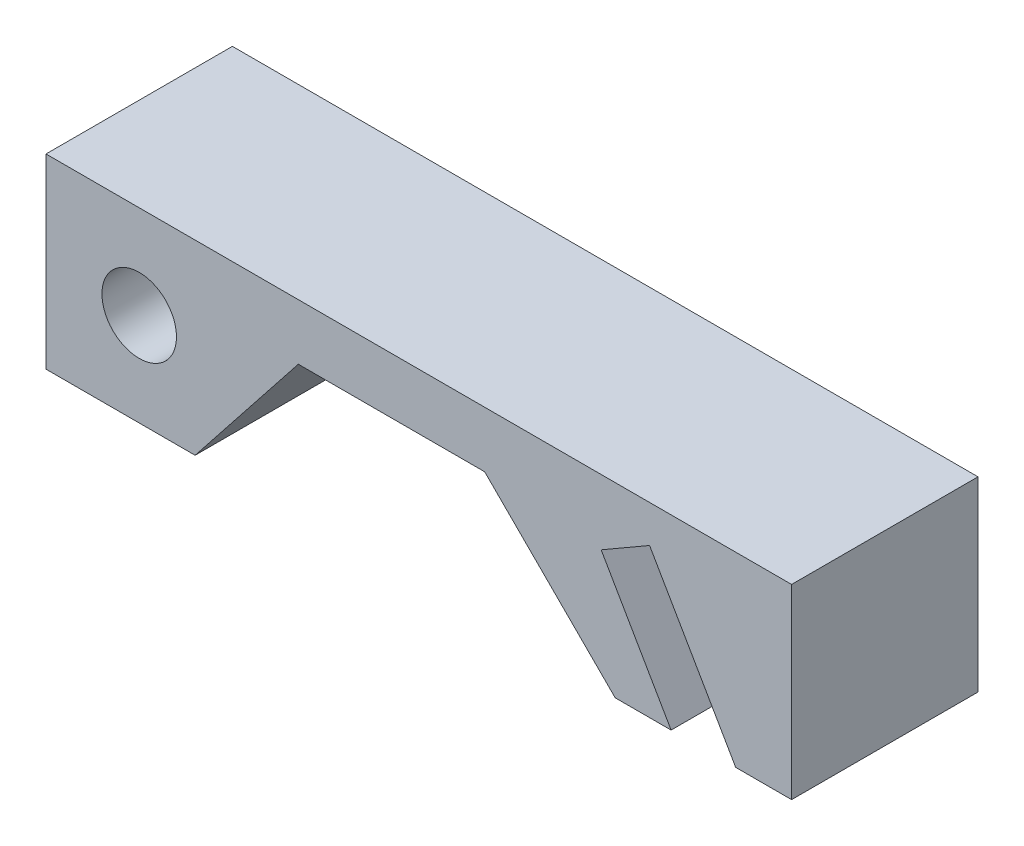
SolidWorks part; units mm, degrees
material "1060 Alloy"
ref_plane "Front Plane" through (0, 0, 0) normal (0, 0, 1) x (1, 0, 0)
ref_plane "Top Plane" through (0, 0, 0) normal (0, 1, 0) x (1, 0, 0)
ref_plane "Right Plane" through (0, 0, 0) normal (1, 0, 0) x (0, 0, -1)
sketch "Sketch2" plane through (0, 0, 0) normal (0, 0, 1) x (1, 0, 0)
  line L0 (0, 0) -> (0, 12.7)
  line L1 (0, 12.7) -> (50.8, 12.7)
  line L2 (50.8, 12.7) -> (50.8, 0)
  line L3 (50.8, 0) -> (46.99, 0)
  line L4 (46.99, 0) -> (41.1241, 10.16)
  line L5 (41.1241, 10.16) -> (37.8246, 8.255)
  line L6 (37.8246, 8.255) -> (42.5906, 0)
  line L7 (42.5906, 0) -> (38.7806, 0)
  line L8 (38.7806, 0) -> (29.8906, 8.89)
  line L9 (29.8906, 8.89) -> (17.1906, 8.89)
  line L10 (17.1906, 8.89) -> (10.16, 0)
  line L11 (10.16, 0) -> (0, 0)
  line L12 (0, 12.7) -> (6.35, 6.35) construction
  line L13 (6.35, 6.35) -> (0, 0) construction
  circle A0 centre (6.35, 6.35) radius 2.54
  dimension "D12" = 5.08
  dimension "D1" = 12.7
  dimension "D2" = 50.8
  dimension "D3" = 3.81
  dimension "D4" = 120
  dimension "D5" = 10.16
  dimension "D6" = 3.81
  dimension "D7" = 3.81
  dimension "D8" = 135
  dimension "D9" = 8.89
  dimension "D10" = 12.7
  dimension "D11" = 10.16
  dimension "D13" = 45
  dimension "D14" = 45
extrude "Boss-Extrude1" add sketch "Sketch2" along normal mid plane 12.7
